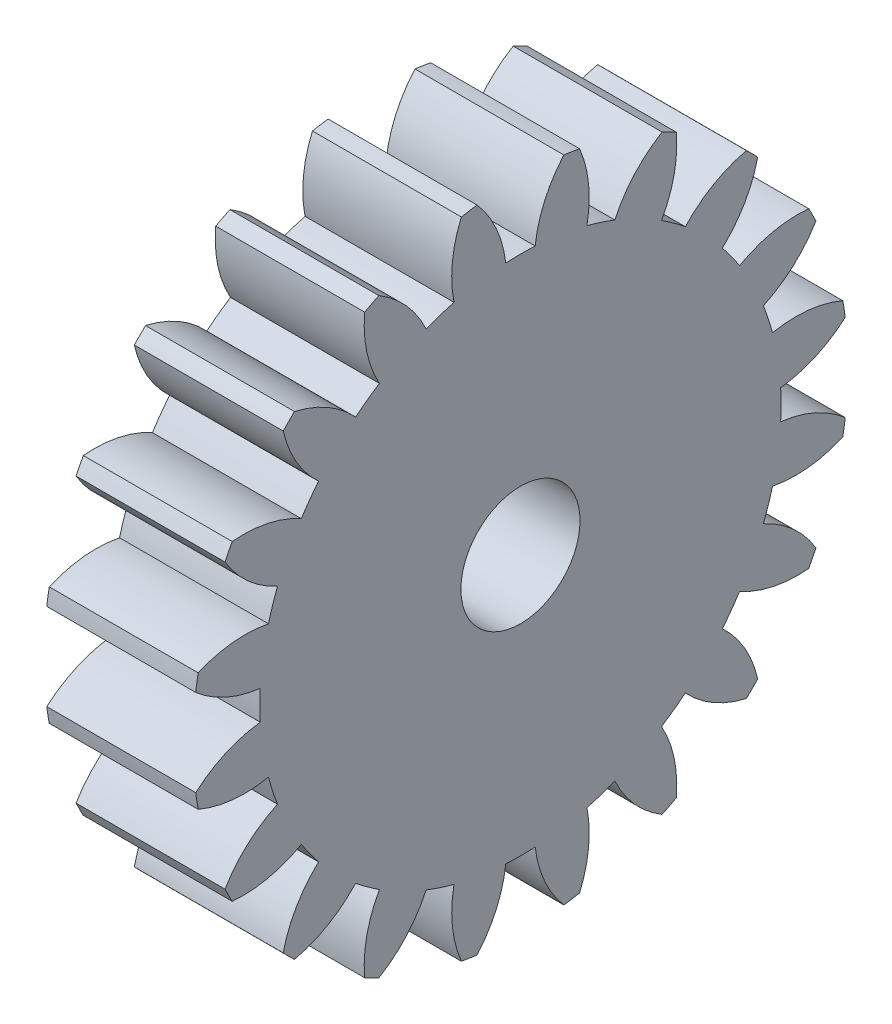
SolidWorks part; units mm, degrees
ref_plane "Plane1" through (0, 0, 0) normal (0, 0, 1) x (1, 0, 0)
ref_plane "Plane2" through (0, 0, 0) normal (0, 1, 0) x (1, 0, 0)
ref_plane "Plane3" through (0, 0, 0) normal (1, 0, 0) x (0, 0, -1)
sketch "HoldingSke" plane through (0, 0, 0) normal (0, 1, 0) x (1, 0, 0)
  line L0 (0, 0) -> (0.4698, -0.171)
  line L1 (-15, 0) -> (100, 0) construction
  line L2 (0, 0) -> (-2.1039, 2.3779)
  line L3 (0, 0) -> (-11.863, 4.5341)
  line L4 (0, 0) -> (8.1152, 2.9537)
  line L5 (0, 0) -> (-46.8476, -17.4728)
  line L6 (0, 0) -> (-8.2896, -5.593)
  line L7 (-2.1039, 2.3779) -> (8.6586, 51.2059)
  line L8 (-76.2, 54.61) -> (-74.8, 54.61)
  line L9 (-71.009, 38.7566) -> (-53.1078, 45.2721)
  line L10 (-76.2, 71.12) -> (104.1128, 71.12)
  line L11 (0, 0) -> (-10, 0)
  line L12 (-76.2, 101.6) -> (-76.133, 101.6)
  line L13 (24.9733, 27.94) -> (52.9518, 28.4284)
  line L14 (24.9733, 27.94) -> (24.9743, 27.94)
  line L15 (24.9733, 27.94) -> (100.4006, 29.5858)
  line L16 (-63.627, -2) -> (-12.827, -2)
  circle A0 centre (0, 0) radius 4
  circle A1 centre (0, 0) radius 17.499
  circle A2 centre (0, 0) radius 37.5
  circle A3 centre (0, 0) radius 4
  dimension "MHD" = 34.998
  dimension "Hub_dia" = 75
  dimension "Bore" = 8
  dimension "MBD" = 8
  dimension "Num_teeth" = 20
  dimension "Pitch" = 0.5
  dimension "Overall_len" = 50
  dimension "Show_teeth" = 20
  dimension "Thickness" = 10
  dimension "OAL" = 50.0001
  dimension "T_dim" = 1.4
  dimension "Ap" = 20
  dimension "H" = 19.05
  dimension "Pitch_radius" = 180.3128
  dimension "Width" = 10
  dimension "Backlash" = 0.067
  dimension "Addendum_fac" = 1
  dimension "Dedendum_fac" = 1.25
  dimension "Clearance_fac" = 0.25
  dimension "Dedendum_add" = 0.001
  dimension "Module" = 2
sketch "BasProSke" plane through (0, 0, 0) normal (0, 1, 0) x (1, 0, 0)
  line L0 (-10, 0) -> (60, 0) construction
  line L1 (0, 0) -> (0, 22)
  line L2 (0, 0) -> (10, 0)
  line L3 (10, 0) -> (10, 22)
  line L4 (10, 22) -> (0, 22)
  dimension "Thickness" = 10
  dimension "Diameter" = 44
revolve "Base-Revolve" add sketch "BasProSke" angle 360 about L0
sketch "TooCutSke" plane through (0, 0, 0) normal (1, 0, 0) x (0, 0, -1)
  line L1 (0, 0) -> (0, 107) construction
  line L2 (0, 0) -> (-1.6864, 19.9288) construction
  line L3 (0, 0) -> (-6.2409, 39.4033) construction
  line L4 (-1.6864, 19.9288) -> (-3.1204, 19.7016) construction
  arc A0 (0.9862, 17.4712) -> (-0.9862, 17.4712) centre (0, 0) ccw
  arc A1 (2.9329, 21.8293) -> (-2.9329, 21.8293) centre (0, 0) ccw
  circle A2 centre (0, 0) radius 20 construction
  circle A3 centre (0, 0) radius 18.7939 construction
  arc A4 (-0.9862, 17.4712) -> (-2.9329, 21.8293) centre (-8.9313, 16.536) ccw
  arc A5 (2.9329, 21.8293) -> (0.9862, 17.4712) centre (8.9313, 16.536) ccw
  dimension "Root_dia" = 34.998
  dimension "Overcut_dia" = 44.0508
  dimension "Pitch_dia" = 40
  dimension "Base_dia" = 37.5877
  dimension "Flank_rad" = 8
  dimension "Half_ang" = 9
  dimension "Half_CT" = 1.4519
extrude "ToothCut" cut sketch "TooCutSke" along normal through all
fillet "Breaks" [suppressed] radius 0.04
fillet "RootFillets" [suppressed] radius 0.501
pattern_circular "TeethCuts" count 20 every 18 about axis through (-10, 0, 0) along (1, 0, 0) of "ToothCut", "RootFillets", "Breaks"
sketch "HubNeaOneSke" plane through (0, 0, 0) normal (-1, 0, 0) x (0, 0, 1)
  circle A0 centre (0, 0) radius 17.499
  dimension "Diameter" = 34.998
extrude "HubNearOne" [suppressed] add sketch "HubNeaOneSke" along normal blind 40.0001
sketch "HubNeaBotSke" plane through (0, 0, 0) normal (-1, 0, 0) x (0, 0, 1)
  circle A0 centre (0, 0) radius 17.499
  dimension "Diameter" = 34.998
extrude "HubNearBoth" [suppressed] add sketch "HubNeaBotSke" along normal blind 20
ref_plane "FarPln" through (10, 0, 0) normal (1, 0, 0) x (0, 0, -1)
sketch "HubFarSke" plane through (10, 0, 0) normal (1, 0, 0) x (0, 0, -1)
  circle A0 centre (0, 0) radius 17.499
  dimension "Diameter" = 34.998
extrude "HubFar" [suppressed] add sketch "HubFarSke" along normal blind 20
sketch "BorSke" plane through (0, 0, 0) normal (1, 0, 0) x (0, 0, -1)
  circle A0 centre (0, 0) radius 4
  dimension "Diameter" = 8
extrude "Bore" cut sketch "BorSke" along normal mid plane 100.0001
sketch "KeySke" plane through (0, 0, 0) normal (1, 0, 0) x (0, 0, -1)
  line L0 (-1.5, 0) -> (-1.5, 5.4)
  line L1 (-1.5, 5.4) -> (1.5, 5.4)
  line L2 (1.5, 5.4) -> (1.5, 0)
  line L3 (0, 0) -> (0, 34) construction
  line L4 (-1.5, 0) -> (1.5, 0)
  dimension "Offset" = 5.4
  dimension "Width" = 3
extrude "Keyway" [suppressed] cut sketch "KeySke" along normal mid plane 100.0001
pattern_circular "Keyway2" [suppressed] count 2 every 90 about axis through (-10, 0, 0) along (1, 0, 0)
equation "' \"Module@HoldingSke\" = 6.35"
equation "' \"Num_teeth@HoldingSke\" = 12"
equation "' \"Ap@HoldingSke\" =  20"
equation "' \"Ap@HoldingSke\" = 20"
equation "' \"Width@HoldingSke\" = 0.5 * 25.4"
equation "' \"Hub_dia@HoldingSke\"= 1 * 25.4"
equation "' \"Hub_dia@HoldingSke\" = 1 * 25.4"
equation "' \"Overall_len@HoldingSke\" = 1.0 * 25.4"
equation "' \"Bore@HoldingSke\" = 0.75 * 25.4"
equation "' \"T_dim@HoldingSke\" = 0.1 * 25.4"
equation "' \"Width@KeySke\" = 0.25 * 25.4"
equation "' \"Show_teeth@HoldingSke\" = 13"
equation "' \"Backlash@HoldingSke\" = 0.009 * 25.4"
equation "' \"Addendum_fac@HoldingSke\" = 1.0"
equation "' \"Dedendum_fac@HoldingSke\" = 1.25"
equation "' \"Dedendum_add@HoldingSke\" = 0.00005 * 25.4"
equation "' \"Clearance_fac@HoldingSke\" = 0.25"
equation "\"Pitch@HoldingSke\" = 1 / \"Module@HoldingSke\""
equation "\"Overcut_dia@TooCutSke\" = (\"Num_teeth@HoldingSke\" + 2 * \"Addendum_fac@HoldingSke\") / \"Pitch@HoldingSke\" + 0.002 * 25.4"
equation "\"Pitch_dia@TooCutSke\" = \"Num_teeth@HoldingSke\" / \"Pitch@HoldingSke\""
equation "\"Base_dia@TooCutSke\" = \"Num_teeth@HoldingSke\" / \"Pitch@HoldingSke\" * cos((\"Ap@HoldingSke\"  * 3.14159265 / 180))"
equation "\"Root_dia@TooCutSke\" = (\"Num_teeth@HoldingSke\" + 2) / \"Pitch@HoldingSke\" - 2 * (\"Addendum_fac@HoldingSke\" + \"Dedendum_fac@HoldingSke\") / \"Pitch@HoldingSke\" - \"Dedendum_add@HoldingSke\" * 2"
equation "\"Half_ang@TooCutSke\" = 180 / \"Num_teeth@HoldingSke\""
equation "\"Half_CT@TooCutSke\" = \"Num_teeth@HoldingSke\" / \"Pitch@HoldingSke\" * sin((3.14159265 / 2 / \"Num_teeth@HoldingSke\")) / 2 - 7 * \"Backlash@HoldingSke\" / 4"
equation "\"Flank_rad@TooCutSke\" = \"Num_teeth@HoldingSke\" / \"Pitch@HoldingSke\" / 5"
equation "\"Radius@RootFillets\" = \"Clearance_fac@HoldingSke\" / \"Pitch@HoldingSke\" + \"Dedendum_add@HoldingSke\""
equation "\"Break_rad@Breaks\" = 0.02 / \"Pitch@HoldingSke\""
equation "\"Thickness@HoldingSke\" = \"Width@HoldingSke\""
equation "\"OAL@HoldingSke\" = \"Thickness@HoldingSke\""
equation "\"MHD@HoldingSke\" = (\"Num_teeth@HoldingSke\" + 2) / \"Pitch@HoldingSke\" - 2 * (\"Addendum_fac@HoldingSke\" + \"Dedendum_fac@HoldingSke\")  / \"Pitch@HoldingSke\" - \"Dedendum_add@HoldingSke\" * 2"
equation "\"MBD@HoldingSke\" = (\"Num_teeth@HoldingSke\" + 2) / \"Pitch@HoldingSke\" - 2 * (\"Addendum_fac@HoldingSke\" + \"Dedendum_fac@HoldingSke\")  / \"Pitch@HoldingSke\" - \"Dedendum_add@HoldingSke\" * 2 - 0.002 * 25.4"
equation "\"MHD@HoldingSke\" = ((sgn( \"MHD@HoldingSke\" - \"Hub_dia@HoldingSke\" )-1)*( \"MHD@HoldingSke\" - \"Hub_dia@HoldingSke\" ))/-2+ \"Hub_dia@HoldingSke\""
equation "\"MBD@HoldingSke\" = ((sgn( \"MBD@HoldingSke\" - \"Bore@HoldingSke\" )-1)*( \"MBD@HoldingSke\" - \"Bore@HoldingSke\" ))/-2+ \"Bore@HoldingSke\""
equation "\"OAL@HoldingSke\" = ((sgn( \"OAL@HoldingSke\" - \"Overall_len@HoldingSke\" )+1)*( \"OAL@HoldingSke\" - \"Overall_len@HoldingSke\" ))/2 + \"Overall_len@HoldingSke\" + 0.000002 * 25.4"
equation "\"Num_teeth@TeethCuts\" = int( \"Show_teeth@HoldingSke\" ) + 1"
equation "\"Num_teeth@TeethCuts\" = ((sgn( \"Num_teeth@TeethCuts\" - \"Num_teeth@HoldingSke\" )-1)*( \"Num_teeth@TeethCuts\" - \"Num_teeth@HoldingSke\" ))/-2+ \"Num_teeth@HoldingSke\""
equation "\"Num_teeth@TeethCuts\" = ((sgn( \"Num_teeth@TeethCuts\" - 2.0)+1)*( \"Num_teeth@TeethCuts\" - 2.0))/2 +2.0"
equation "\"Angle@TeethCuts\" = 360.0 / \"Num_teeth@HoldingSke\""
equation "\"Diameter@BasProSke\" = (\"Num_teeth@HoldingSke\" + 2 * \"Addendum_fac@HoldingSke\") / \"Pitch@HoldingSke\""
equation "\"Thickness@BasProSke\"  = \"Thickness@HoldingSke\""
equation "' \"Fillet_rad@BasProSke\" =  \"Thickness@HoldingSke\" * 0.05"
equation "' \"Fillet_rad@BasProSke\" = \"Thickness@HoldingSke\" * 0.05"
equation "\"MHD@HoldingSke\" = ((sgn( \"MHD@HoldingSke\" - \"Root_dia@TooCutSke\" )-1)*( \"MHD@HoldingSke\" - \"Root_dia@TooCutSke\" ))/-2+ \"Root_dia@TooCutSke\""
equation "\"Diameter@HubNeaOneSke\" = \"MHD@HoldingSke\""
equation "\"Length@HubNearOne\" = \"OAL@HoldingSke\" - \"Thickness@BasProSke\""
equation "\"Diameter@HubNeaBotSke\" = \"MHD@HoldingSke\""
equation "\"Length@HubNearBoth\" = ( \"OAL@HoldingSke\" - \"Thickness@BasProSke\" ) / 2.0"
equation "\"Thickness@FarPln\" = \"Thickness@BasProSke\""
equation "\"Diameter@HubFarSke\" = \"MHD@HoldingSke\""
equation "\"Length@HubFar\" = ( \"OAL@HoldingSke\" - \"Thickness@BasProSke\" ) / 2.0"
equation "\"Diameter@BorSke\" = \"MBD@HoldingSke\""
equation "\"D1@Bore\" = \"OAL@HoldingSke\" * 2.0"
equation "\"D1@Keyway\" = \"OAL@HoldingSke\" * 2.0"
equation "\"Offset@KeySke\" = \"T_dim@HoldingSke\" + \"MBD@HoldingSke\" / 2.0"
